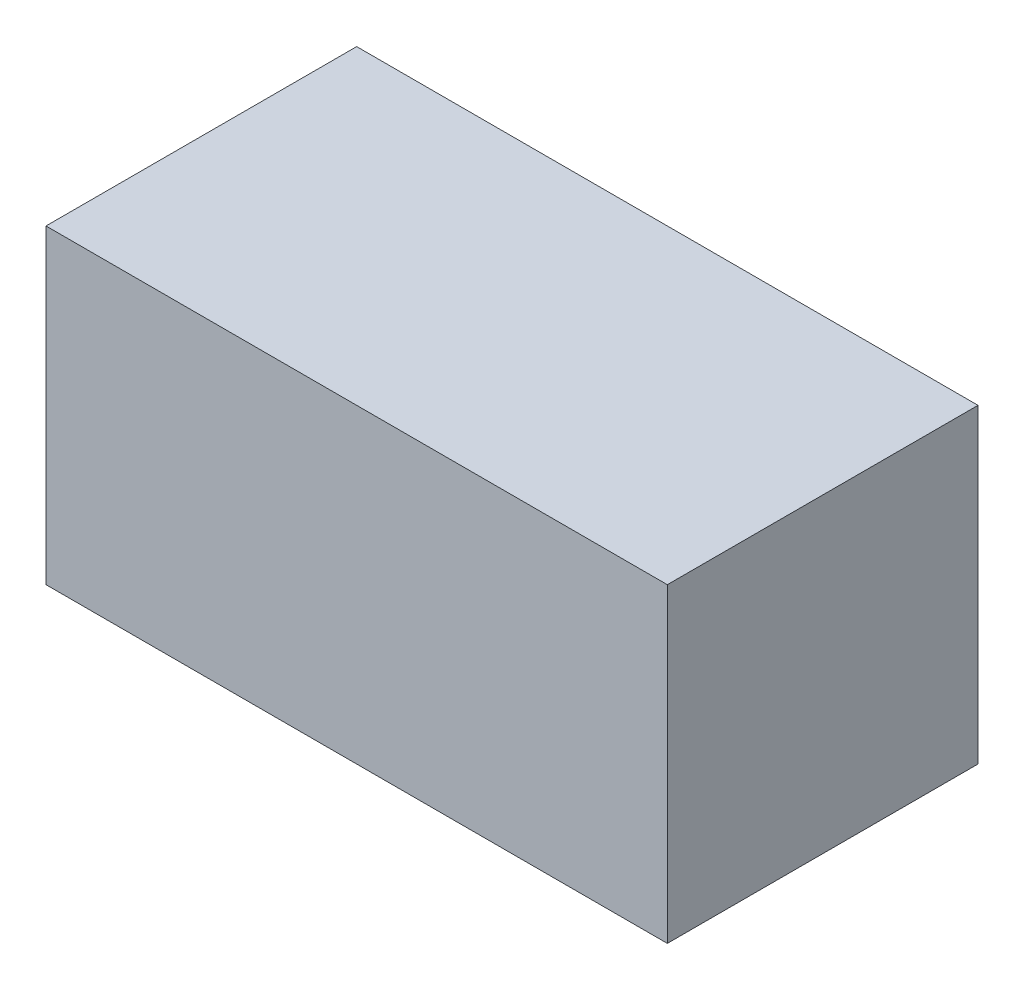
SolidWorks part; units mm, degrees
ref_plane "Front Plane" through (0, 0, 0) normal (0, 0, 1) x (1, 0, 0)
ref_plane "Top Plane" through (0, 0, 0) normal (0, 1, 0) x (1, 0, 0)
ref_plane "Right Plane" through (0, 0, 0) normal (1, 0, 0) x (0, 0, -1)
sketch "Sketch1" plane through (0, 0, 0) normal (0, 0, 1) x (1, 0, 0)
  line L0 (1600, -1450) -> (1600, -1800)
  line L1 (1600, -1800) -> (2300, -1800)
  line L2 (2300, -1800) -> (2300, -1450)
  line L3 (2300, -1450) -> (1600, -1450)
extrude "Boss-Extrude1" add sketch "Sketch1" along normal blind 350
